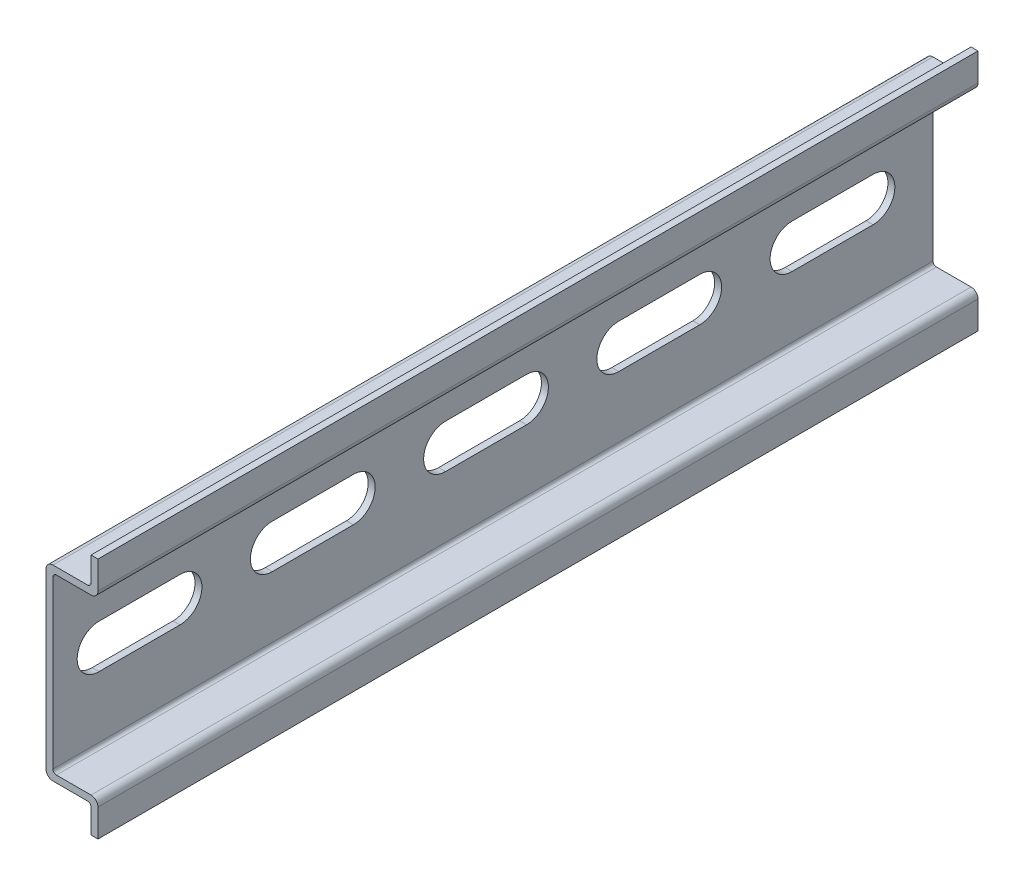
SolidWorks part; units mm, degrees
ref_plane "Front Plane" through (0, 0, 0) normal (0, 0, 1) x (1, 0, 0)
ref_plane "Top Plane" through (0, 0, 0) normal (0, 1, 0) x (1, 0, 0)
ref_plane "Right Plane" through (0, 0, 0) normal (1, 0, 0) x (0, 0, -1)
sketch "Sketch1" plane through (0, 0, 0) normal (0, 0, 1) x (1, 0, 0)
  line L0 (0, 0) -> (7.5, 0) construction
  line L1 (0, 17.5) -> (7.5, 17.5) construction
  line L2 (0, 17.5) -> (0, -17.5) construction
  line L3 (0, -17.5) -> (7.5, -17.5) construction
  line L4 (7.5, 17.5) -> (7.5, -17.5) construction
  line L5 (7.5, 17.5) -> (6.5, 17.5)
  line L6 (6.5, 17.5) -> (6.5, 14)
  line L7 (6, 13.5) -> (1, 13.5)
  line L8 (0, 12.5) -> (0, -12.5)
  line L9 (7.5, 17.5) -> (7.5, 13.5)
  line L10 (6.5, 12.5) -> (1.5, 12.5)
  line L11 (1, 12) -> (1, -12)
  line L12 (6.5, -12.5) -> (1.5, -12.5)
  line L13 (7.5, -17.5) -> (7.5, -13.5)
  line L14 (6, -13.5) -> (1, -13.5)
  line L15 (6.5, -17.5) -> (6.5, -14)
  line L16 (7.5, -17.5) -> (6.5, -17.5)
  line L17 (6.3536, 13.6464) -> (7.2071, 12.7929) construction
  line L18 (1.1464, 12.3536) -> (0.2929, 13.2071) construction
  arc A0 (1.5, 12.5) -> (1, 12) centre (1.5, 12) ccw
  arc A1 (1, 13.5) -> (0, 12.5) centre (1, 12.5) ccw
  arc A2 (7.5, 13.5) -> (6.5, 12.5) centre (6.5, 13.5) cw
  arc A3 (6, 13.5) -> (6.5, 14) centre (6, 14) ccw
  arc A4 (1, -13.5) -> (0, -12.5) centre (1, -12.5) cw
  arc A5 (1.5, -12.5) -> (1, -12) centre (1.5, -12) cw
  arc A6 (7.5, -13.5) -> (6.5, -12.5) centre (6.5, -13.5) ccw
  arc A7 (6, -13.5) -> (6.5, -14) centre (6, -14) cw
  dimension "D5" = 1
  dimension "D6" = 0.5
  dimension "D1" = 35
  dimension "D2" = 7.5
  dimension "D3" = 1
  dimension "D4" = 27
extrude "Boss-Extrude1" add sketch "Sketch1" along normal mid plane 1000
sketch "Sketch2" plane through (0, 0, 0) normal (1, 0, 0) x (0, 0, -1)
  line L0 (-493.35, 0) -> (-481.65, 0) construction
  line L1 (-493.35, 3.15) -> (-481.65, 3.15)
  line L2 (-493.35, -3.15) -> (-481.65, -3.15)
  line L3 (-487.5, 0) -> (-500, 0) construction
  line L4 (-500, 12.5) -> (-500, -12.5) construction
  line L5 (-487.5, 0) -> (-462.5, 0) construction
  line L6 (-462.5, 0) -> (-437.5, 0) construction
  arc A0 (-493.35, 3.15) -> (-493.35, -3.15) centre (-493.35, 0) ccw
  arc A1 (-481.65, -3.15) -> (-481.65, 3.15) centre (-481.65, 0) ccw
  point P2 (-487.5, 0)
  dimension "D1" = 6.3
  dimension "D2" = 18
  dimension "D4" = 12.5
  dimension "D3" = 25
extrude "Cut-Extrude1" cut sketch "Sketch2" along normal up to vertex (7.5 mm away) up to point (7.5, 0, 0)
pattern_linear "LPattern1" count 40 spacing 25 along (0, 0, -1) of "Cut-Extrude1"
sketch "Sketch3" plane through (0, 0, 500) normal (0, 0, 1) x (1, 0, 0)
  line L1 (-4.8132, 19.3433) -> (13.3383, 19.3433)
  line L2 (-4.8132, 19.3433) -> (-4.8132, -19.6183)
  line L3 (-4.8132, -19.6183) -> (13.3383, -19.6183)
  line L4 (13.3383, 19.3433) -> (13.3383, -19.6183)
  line L5 (4.2625, -19.6183) -> (4.2625, 19.3433) construction
  line L6 (-4.8132, -0.1375) -> (13.3383, -0.1375) construction
  point P100 (4.2625, -0.1375)
extrude "Cut-Extrude2" cut sketch "Sketch3" against normal through all from offset 127 offset against normal yes
equation "\"D4@Sketch2\" = \"D3@Sketch2\" / 2"
equation "\"D3@LPattern1\" = \"D3@Sketch2\""
equation "\"D1@LPattern1\" = \"D1@Boss-Extrude1\" / \"D3@LPattern1\""
